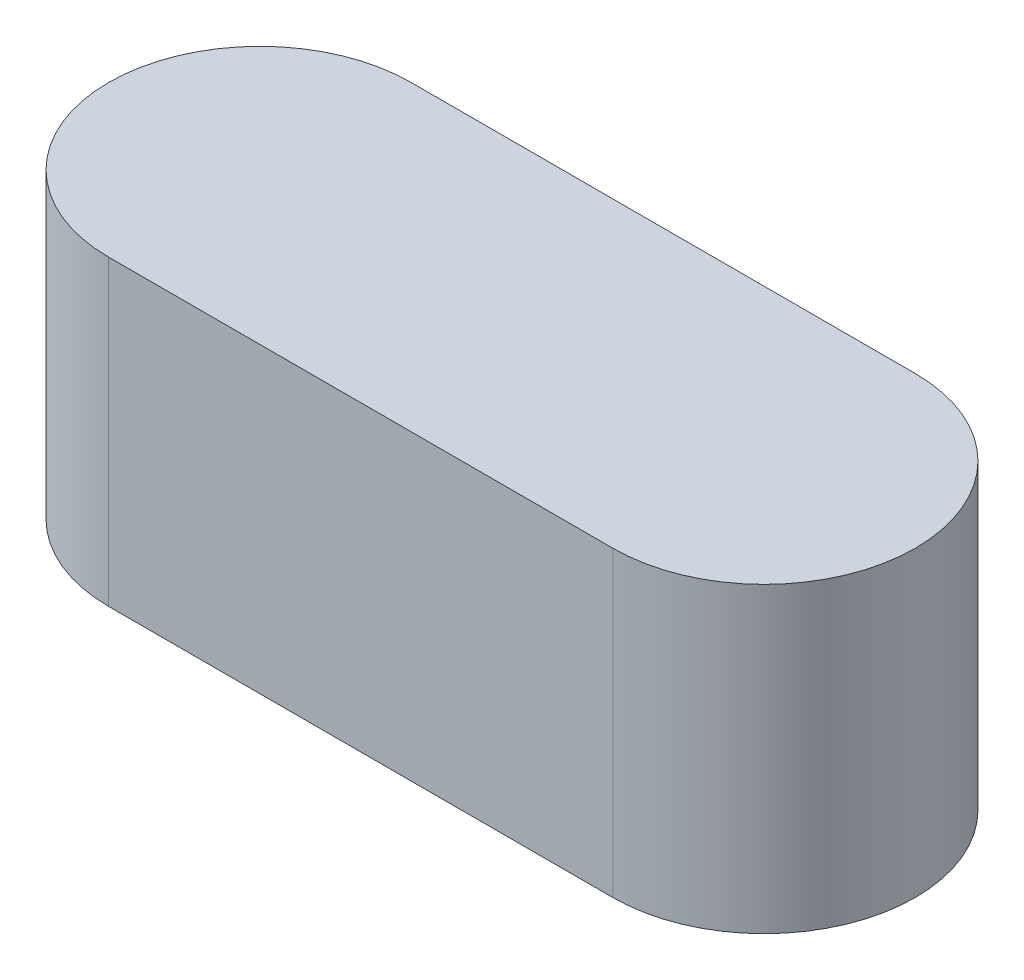
SolidWorks part; units mm, degrees
ref_plane "前视基准面" through (0, 0, 0) normal (0, 0, 1) x (1, 0, 0)
ref_plane "上视基准面" through (0, 0, 0) normal (0, 1, 0) x (1, 0, 0)
ref_plane "右视基准面" through (0, 0, 0) normal (1, 0, 0) x (0, 0, -1)
sketch "草图1" plane through (0, 0, 0) normal (0, 1, 0) x (1, 0, 0)
  line L0 (0, 0) -> (10, 0) construction
  line L1 (-55, 0) -> (55, 0) construction
  line L2 (0, 3) -> (10, 3)
  line L3 (0, -3) -> (10, -3)
  arc A0 (0, 3) -> (0, -3) centre (0, 0) ccw
  arc A1 (10, -3) -> (10, 3) centre (10, 0) ccw
  point P5 (5, 0)
  dimension "D2" = 6
  dimension "D1" = 10
extrude "凸台-拉伸1" add sketch "草图1" along normal blind 6
